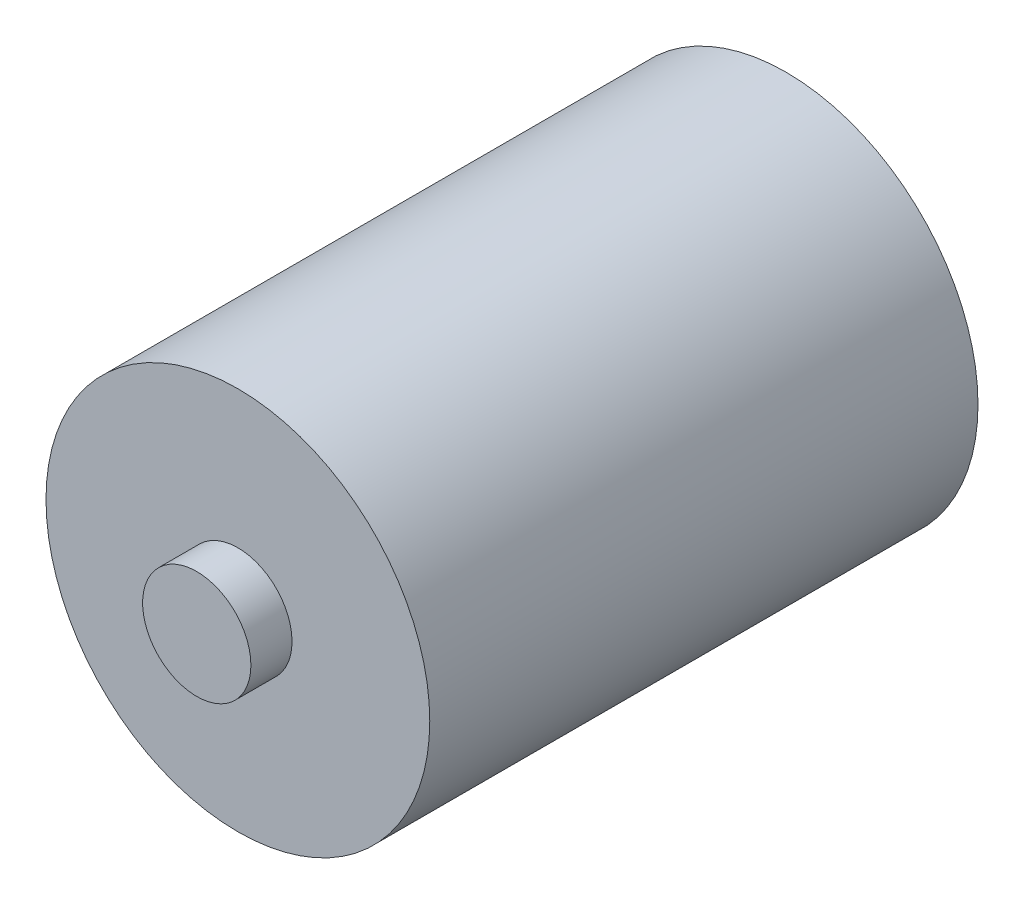
SolidWorks part; units mm, degrees
ref_plane "Front Plane" through (0, 0, 0) normal (0, 0, 1) x (1, 0, 0)
ref_plane "Top Plane" through (0, 0, 0) normal (0, 1, 0) x (1, 0, 0)
ref_plane "Right Plane" through (0, 0, 0) normal (1, 0, 0) x (0, 0, -1)
sketch "Sketch3" plane through (0, 0, 0) normal (0, 0, 1) x (1, 0, 0)
  circle A0 centre (0, 0) radius 70
  dimension "D2" = 140
  dimension "D1" = 0
extrude "Boss-Extrude1" add sketch "Sketch3" along normal blind 200
sketch "Sketch4" plane through (0, 0, 200) normal (0, 0, 1) x (1, 0, 0)
  circle A0 centre (0, 0) radius 19.75
  circle A1 centre (0, 0) radius 70 construction
  dimension "D1" = 39.5
  dimension "D2" = 0
extrude "Boss-Extrude2" add sketch "Sketch4" along normal blind 15
sketch "Sketch5" plane through (0, 0, 0) normal (0, 0, -1) x (-1, 0, 0)
  circle A0 centre (0, 0) radius 31.5
  circle A1 centre (0, 0) radius 70 construction
  dimension "D1" = 0
  dimension "D2" = 63
extrude "Boss-Extrude3" add sketch "Sketch5" along normal blind 7
sketch "Sketch6" plane through (0, 0, -7) normal (0, 0, -1) x (-1, 0, 0)
  circle A0 centre (8.3371, 8.5802) radius 13.0059
  circle A1 centre (-13.658, -10.6157) radius 5.9131
extrude "Boss-Extrude4" add sketch "Sketch6" along normal blind 10
